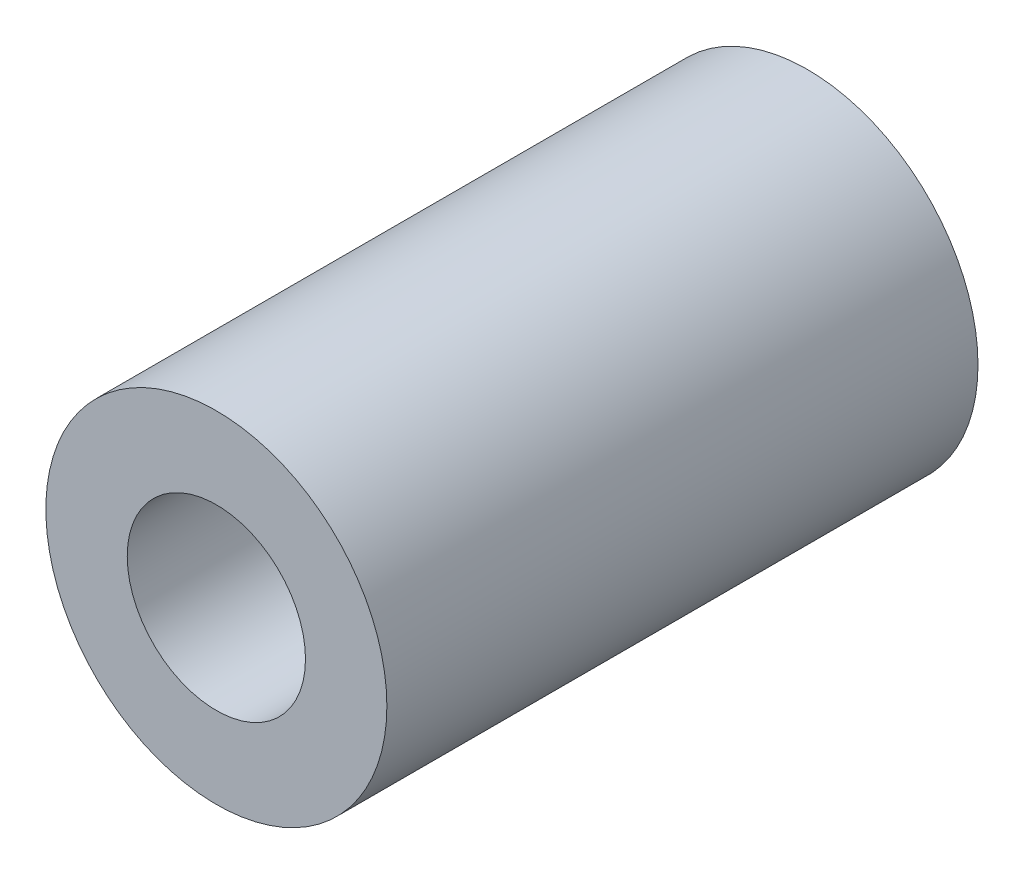
SolidWorks part; units mm, degrees
material "6061-T6 (SS)"
ref_plane "Front Plane" through (0, 0, 0) normal (0, 0, 1) x (1, 0, 0)
ref_plane "Top Plane" through (0, 0, 0) normal (0, 1, 0) x (1, 0, 0)
ref_plane "Right Plane" through (0, 0, 0) normal (1, 0, 0) x (0, 0, -1)
sketch "Sketch1" plane through (0, 0, 0) normal (0, 0, 1) x (1, 0, 0)
  circle A0 centre (0, 0) radius 4.7625
  circle A1 centre (0, 0) radius 2.4892
  dimension "D1" = 9.525
  dimension "D2" = 4.9784
extrude "Boss-Extrude1" add sketch "Sketch1" along normal blind 16.51
